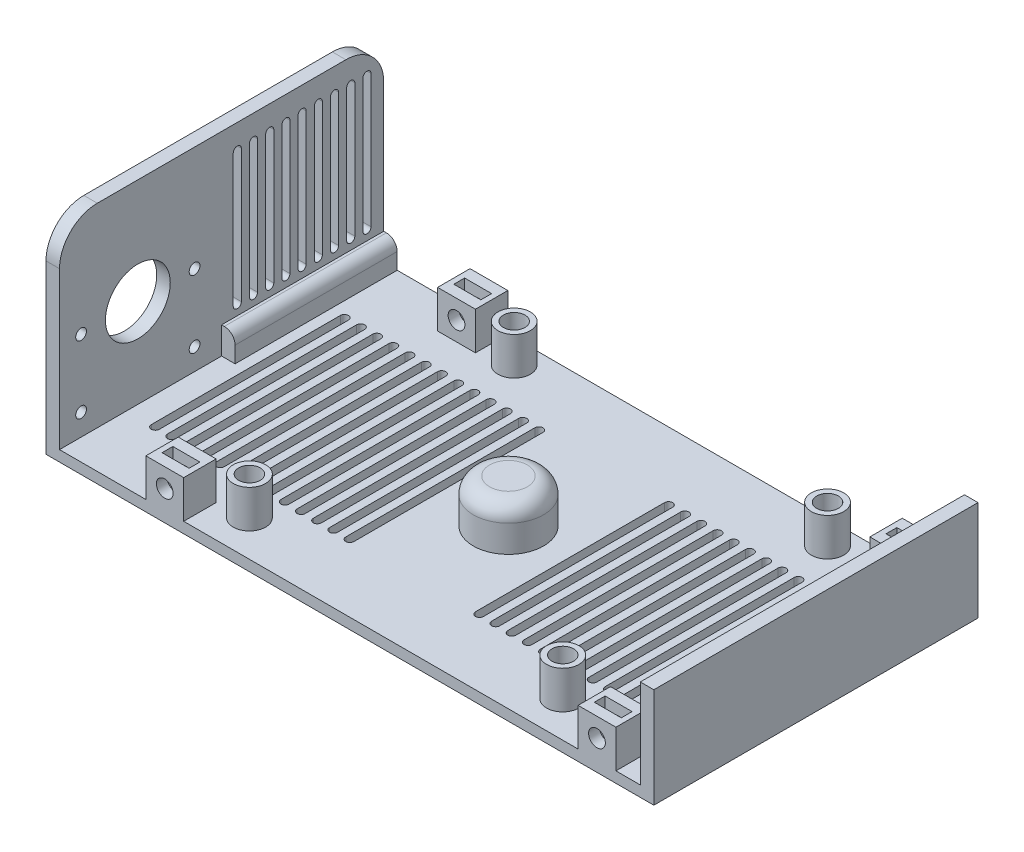
SolidWorks part; units mm, degrees
ref_plane "Front Plane" through (0, 0, 0) normal (0, 0, 1) x (1, 0, 0)
ref_plane "Top Plane" through (0, 0, 0) normal (0, 1, 0) x (1, 0, 0)
ref_plane "Right Plane" through (0, 0, 0) normal (1, 0, 0) x (0, 0, -1)
sketch "Sketch1" plane through (0, 0, 0) normal (0, 1, 0) x (1, 0, 0)
  line L1 (0, 0) -> (110, 0)
  line L2 (0, 0) -> (0, -60)
  line L3 (0, -60) -> (110, -60)
  line L4 (110, 0) -> (110, -60)
  dimension "D1" = 60
  dimension "D2" = 110
extrude "Boss-Extrude1" add sketch "Sketch1" along normal blind 2
sketch "Sketch2" plane through (0, 2, 0) normal (0, 1, 0) x (1, 0, 0)
  circle A0 centre (28.5, -4.35) radius 3
  circle A1 centre (28.5, -4.35) radius 1.5 construction
  circle A2 centre (86.5, -4.35) radius 3
  circle A3 centre (28.5, -53.35) radius 3
  circle A4 centre (86.5, -53.35) radius 3
  circle A5 centre (28.5, -53.35) radius 1.5 construction
  circle A6 centre (86.5, -53.35) radius 1.5 construction
  circle A7 centre (86.5, -4.35) radius 1.5 construction
  dimension "D1" = 6
extrude "Boss-Extrude2" add sketch "Sketch2" along normal blind 7
sketch "Sketch3" plane through (0, 0, 0) normal (-1, 0, 0) x (0, 0, 1)
  line L0 (60, 2) -> (60, 0) construction
  line L1 (0, 0) -> (60, 0)
  line L2 (0, 0) -> (0, 31)
  line L3 (7, 38) -> (53, 38)
  line L4 (60, 0) -> (60, 31)
  line L5 (58, 28) -> (33, 28) construction
  arc A0 (53, 38) -> (60, 31) centre (53, 31) cw
  arc A1 (0, 31) -> (7, 38) centre (7, 31) cw
  dimension "D2" = 7
  dimension "D1" = 10
extrude "Boss-Extrude3" add sketch "Sketch3" along normal blind 2.5
sketch "Sketch5" plane through (-2.5, 0, 0) normal (-1, 0, 0) x (0, 0, 1)
  circle A0 centre (45.5, 18.5) radius 6
  circle A1 centre (45.5, 18.5) radius 3.8 construction
  dimension "D1" = 12
extrude "Cut-Extrude1" cut sketch "Sketch5" against normal up to next
sketch "Sketch6" plane through (-2.5, 0, 0) normal (-1, 0, 0) x (0, 0, 1)
  circle A0 centre (56, 18.5) radius 2.5
  circle A1 centre (35, 18.5) radius 2.5
  circle A2 centre (35, 6) radius 2.5
  circle A3 centre (56, 6) radius 2.5
  circle A4 centre (56, 18.5) radius 1.5 construction
  circle A5 centre (56, 6) radius 1.5 construction
  circle A6 centre (35, 6) radius 1 construction
  circle A7 centre (35, 18.5) radius 1 construction
  dimension "D1" = 5
extrude "Cut-Extrude2" cut sketch "Sketch6" against normal blind 1
sketch "Sketch7" plane through (-2.5, 0, 0) normal (-1, 0, 0) x (0, 0, 1)
  circle A0 centre (35, 18.5) radius 1
  circle A1 centre (35, 6) radius 1
  circle A2 centre (56, 6) radius 1
  circle A3 centre (56, 18.5) radius 1
  circle A4 centre (35, 18.5) radius 2.5 construction
  circle A5 centre (35, 6) radius 2.5 construction
  circle A6 centre (56, 18.5) radius 2.5 construction
  circle A7 centre (56, 6) radius 2.5 construction
  dimension "D1" = 2
extrude "Cut-Extrude7" cut sketch "Sketch7" along direction (1, 0, 0) on the side against the normal up to next (2.5 mm away)
sketch "Sketch8" plane through (0, 0, 60) normal (0, 0, 1) x (1, 0, 0)
  line L0 (0, 2) -> (110, 2) construction
  line L1 (95.9805, 2) -> (102.9805, 2)
  line L2 (95.9805, 2) -> (95.9805, 9)
  line L3 (95.9805, 9) -> (102.9805, 9)
  line L4 (102.9805, 2) -> (102.9805, 9)
  dimension "D1" = 7
  dimension "D2" = 7
extrude "Boss-Extrude5" add sketch "Sketch8" against normal blind 6
ref_plane "Plane1" through (0, 0, 58) normal (0, 0, 1) x (1, 0, 0)
sketch "Sketch9" plane through (0, 0, 58) normal (0, 0, 1) x (1, 0, 0)
  line L0 (91.3288, 5.5) -> (105.2745, 5.5) construction
  line L1 (99.4805, 2.6132) -> (101.9805, 4.0566)
  line L2 (101.9805, 4.0566) -> (101.9805, 9)
  line L3 (96.9805, 9) -> (101.9805, 9)
  line L5 (96.9805, 9) -> (96.9805, 4.0566)
  line L6 (96.9805, 4.0566) -> (99.4805, 2.6132)
  line L7 (99.4805, 11.4044) -> (99.4805, -1.21) construction
  line L8 (95.9805, 9) -> (95.9805, 2) construction
  line L9 (102.9805, 2) -> (102.9805, 9) construction
  line L10 (102.9805, 9) -> (95.9805, 9) construction
  line L11 (99.4805, 8.3868) -> (96.9805, 6.9434) [skipped]
  line L12 (101.9805, 6.9434) -> (99.4805, 8.3868) [skipped]
  circle A0 centre (99.4805, 5.5) radius 2.5 construction
  point P16 (99.4805, 5.5)
  dimension "D1" = 5
  dimension "D2" = 3.5
extrude "Cut-Extrude9" cut sketch "Sketch9" against normal blind 2
sketch "Sketch11" plane through (0, 0, 60) normal (0, 0, 1) x (1, 0, 0)
  line L0 (99.4805, 10.3782) -> (99.4805, 2.3881) construction
  line L1 (95.9805, 9) -> (95.9805, 2) construction
  line L2 (102.9805, 2) -> (102.9805, 9) construction
  line L3 (95.119, 5.5) -> (103.6709, 5.5) construction
  line L4 (102.9805, 9) -> (95.9805, 9) construction
  circle A0 centre (99.4805, 5.5) radius 1.55
  dimension "D2" = 3.1
  dimension "D1" = 3.5
extrude "Cut-Extrude11" cut sketch "Sketch11" along direction (0, 0, -1) on the side against the normal through all
pattern_linear "LPattern1" count 2 spacing 80 along (-1, 0, 0) count 2 spacing 54 along (0, 0, -1) of "Boss-Extrude5", "Cut-Extrude9", "Cut-Extrude11"
sketch "Sketch12" plane through (110, 0, 0) normal (1, 0, 0) x (0, 0, -1)
  line L0 (0, 31) -> (0, 2) construction
  line L2 (-60, 2) -> (0, 2)
  line L3 (-60, 2) -> (-60, 18.5128)
  line L4 (-60, 18.5128) -> (0, 18.5128)
  line L5 (0, 2) -> (0, 18.5128)
extrude "Boss-Extrude6" add sketch "Sketch12" against normal blind 2.5
sketch "Sketch14" plane through (0, 9, 0) normal (0, 1, 0) x (1, 0, 0)
  circle A0 centre (28.5, -53.35) radius 2
  circle A1 centre (86.5, -53.35) radius 2
  circle A2 centre (28.5, -4.35) radius 2
  circle A3 centre (86.5, -4.35) radius 2
  dimension "D1" = 4
extrude "Cut-Extrude12" cut sketch "Sketch14" against normal blind 6.5
sketch "Sketch15" plane through (-2.5, 0, 0) normal (-1, 0, 0) x (0, 0, 1)
  line L0 (3.0929, 33.4682) -> (3.0929, 8.8931) construction
  line L1 (3.8429, 33.4682) -> (3.8429, 8.8931)
  line L2 (2.3429, 33.4682) -> (2.3429, 8.8931)
  arc A0 (3.8429, 33.4682) -> (2.3429, 33.4682) centre (3.0929, 33.4682) ccw
  arc A1 (2.3429, 8.8931) -> (3.8429, 8.8931) centre (3.0929, 8.8931) ccw
  point P2 (3.0929, 21.1806)
  dimension "D1" = 1.5
extrude "Cut-Extrude15" cut sketch "Sketch15" along direction (1, 0, 0) on the side against the normal up to next (2.5 mm away)
pattern_linear "LPattern5" count 9 spacing 3 along (0, 0, 1) of "Cut-Extrude15"
sketch "Sketch17" plane through (0, 2, 0) normal (0, 1, 0) x (1, 0, 0)
  line L0 (123.5011, -30) -> (-22.0005, -30) construction
  line L1 (53.75, -71.9034) -> (53.75, 10.5934) construction
  line L2 (95.9805, 0) -> (22.9805, 0) construction
  line L3 (22.9805, -60) -> (95.9805, -60) construction
  line L4 (-2.5, -53) -> (-2.5, -7) construction
  line L5 (110, 0) -> (110, -60) construction
  circle A0 centre (53.75, -30.655) radius 6.5
  dimension "D1" = 13
extrude "Boss-Extrude7" add sketch "Sketch17" along normal blind 8
sketch "Sketch18" plane through (0, 0, 0) normal (0, -1, 0) x (1, 0, 0)
  circle A0 centre (53.75, 30.655) radius 4.5
  circle A1 centre (53.75, 30.655) radius 6.5 construction
  dimension "D1" = 9
extrude "Cut-Extrude16" cut sketch "Sketch18" against normal blind 8
fillet "Fillet2" radius 3 1 edges at (53.75, 10, 37.155)
sketch "Sketch19" plane through (0, 2, 0) normal (0, 1, 0) x (1, 0, 0)
  line L0 (5.2314, -12.5) -> (5.2314, -47.5) construction
  line L1 (5.9814, -12.5) -> (5.9814, -47.5)
  line L2 (4.4814, -12.5) -> (4.4814, -47.5)
  line L3 (-14.198, -30) -> (114.4364, -30) construction
  line L4 (95.9805, 0) -> (22.9805, 0) construction
  line L5 (22.9805, -60) -> (95.9805, -60) construction
  arc A0 (5.9814, -12.5) -> (4.4814, -12.5) centre (5.2314, -12.5) ccw
  arc A1 (4.4814, -47.5) -> (5.9814, -47.5) centre (5.2314, -47.5) ccw
  point P2 (5.2314, -30)
  dimension "D2" = 35
  dimension "D1" = 1.5
extrude "Cut-Extrude18" cut sketch "Sketch19" along direction (0, 1, 0) on the side against the normal up to next (2 mm away)
pattern_linear "LPattern7" count 34 spacing 3 along (1, 0, 0) skipping (13, 0), (14, 0), (15, 0), (16, 0), (17, 0), (18, 0), (19, 0) of "Cut-Extrude18"
sketch "Sketch21" plane through (0, 0, 0) normal (0, 0, -1) x (-1, 0, 0)
  line L0 (2.5, 31) -> (2.5, 0) construction
  line L1 (0, 2) -> (-2.5, 2)
  line L2 (0, 2) -> (0, 7)
  line L3 (0, 7) -> (-0.5, 7)
  line L4 (-2.5, 2) -> (-2.5, 5)
  line L5 (-110, 0) -> (2.5, 0) construction
  arc A0 (-0.5, 7) -> (-2.5, 5) centre (-0.5, 5) ccw
  point P11 (-2.5, 7)
  dimension "D3" = 2
  dimension "D1" = 5
  dimension "D2" = 7
extrude "Boss-Extrude9" add sketch "Sketch21" against normal blind 30
